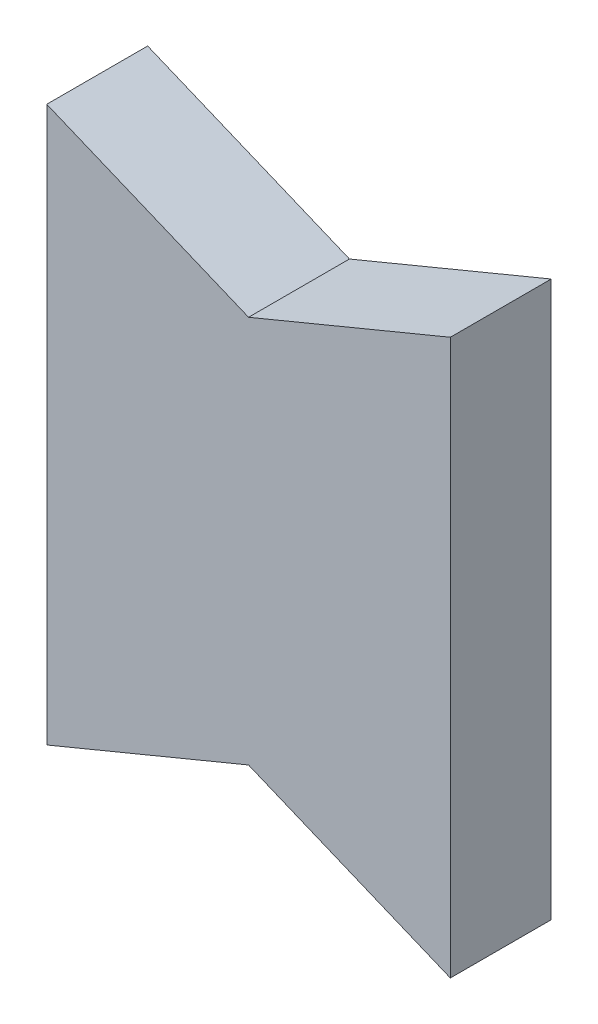
SolidWorks part; units mm, degrees
ref_plane "Ebene vorne" through (0, 0, 0) normal (1, 0, 0) x (0, 1, 0)
ref_plane "Ebene oben" through (0, 0, 0) normal (0, 0, 1) x (0, 1, 0)
ref_plane "Ebene rechts" through (0, 0, 0) normal (0, 1, 0) x (-1, 0, 0)
sketch "Skizze1" plane through (0, 0, 0) normal (0, 0, 1) x (0, 1, 0)
  line L0 (-5.5, 4) -> (5.5, 4)
  line L1 (5.5, 4) -> (3.8431, 0)
  line L2 (3.8431, 0) -> (-3.8431, 0)
  line L3 (-3.8431, 0) -> (-5.5, 4)
  point P2 (0, 0)
  point P8 (0, 4)
  point P14 (0, 0)
  dimension "D1" = 4
  dimension "D2" = 11
  dimension "D3" = 67.5
extrude "Aufsatz-Linear austragen1" add sketch "Skizze1" along normal blind 2
mirror "Spiegeln1" about plane through (0, 3.8431, 2) normal (-1, 0, 0) of "Aufsatz-Linear austragen1"
equation "\"wall_thickness\"= 2mm"
equation "\"D1@Skizze1\"=\"wall_thickness\"*2"
equation "\"D2@Skizze1\"=\"grid_unit\"-7*\"wall_thickness\""
equation "\"grid_unit\"= 25mm"
equation "\"D1@Aufsatz-Linear austragen1\"=\"wall_thickness\""
